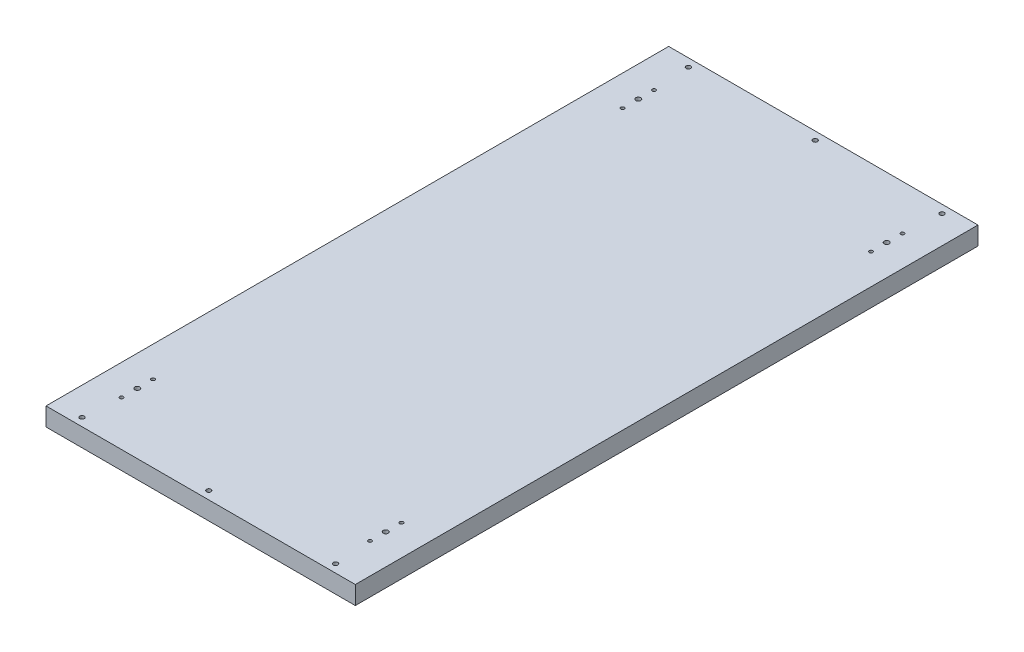
SolidWorks part; units mm, degrees
ref_plane "Front Plane" through (0, 0, 0) normal (0, 0, 1) x (1, 0, 0)
ref_plane "Top Plane" through (0, 0, 0) normal (0, 1, 0) x (1, 0, 0)
ref_plane "Right Plane" through (0, 0, 0) normal (1, 0, 0) x (0, 0, -1)
other "Bounding Box"
ref_plane "Default Plane" through (152.5, 9, -307) normal (-1, 0, 0) x (0, 0, 1)
sketch "Sketch1" plane through (0, 0, 0) normal (0, 1, 0) x (1, 0, 0)
  line L0 (-152.5, 307) -> (152.5, -307) construction
  line L1 (-152.5, 307) -> (152.5, 307)
  line L2 (-152.5, 307) -> (-152.5, -307)
  line L3 (-152.5, -307) -> (152.5, -307)
  line L4 (152.5, 307) -> (152.5, -307)
  line L5 (152.5, 307) -> (-152.5, -307) construction
  point P0 (0, 0)
  dimension "D1" = 305
  dimension "D2" = 614
extrude "Boss-Extrude1" add sketch "Sketch1" along normal mid plane 18 contours L4 L3 L2 L1
hole_wizard "CSK for #8 Flat Head Machine Screw (100)1" positions "Sketch2" profile "Sketch3" countersink size "#8" standard "ANSI Inch" end condition through all
sketch "Sketch2" plane through (-75, -9, 0) normal (0, -1, 0) x (0, 0, -1)
  line L3 (-307, -77.5) -> (-307, 227.5) construction
  line L4 (307, 227.5) -> (-307, 227.5) construction
  line L5 (-307, 75) -> (307, 75) construction
  line L6 (307, -77.5) -> (307, 227.5) construction
  point P9 (-299, 75)
  point P14 (-299, -50)
  point P23 (-299, 200)
  dimension "D1" = 8
  dimension "D2" = 125
sketch "Sketch3" plane through (0, -9, 299) normal (1, 0, 0) x (0, 0, -1)
  line L0 (0, 0) -> (0, 18)
  line L1 (0, 18) -> (2.2479, 18)
  line L2 (2.2479, 18) -> (2.2479, 1.6518)
  line L3 (2.2479, 1.6518) -> (4.2164, 0)
  line L5 (4.2164, 0) -> (0, 0)
  line L6 (-2.2479, 1.6518) -> (-4.2164, 0) construction
  line L11 (0, -6.35) -> (0, 107.95) construction
  dimension "Thru Hole Dia." = 4.4958
  dimension "Thru Hole Depth" = 18
  dimension "Near C'Sink Dia." = 8.4328
  dimension "Near C'Sink Angle" = 100
mirror "Mirror1" about plane through (0, 0, 0) normal (0, 0, 1) of "CSK for #8 Flat Head Machine Screw (100)1"
hole_wizard "#8-36 Tapped Hole1" positions "Sketch6" profile "Sketch5" tap size "#8-36" standard "ANSI Inch" end condition through all
sketch "Sketch6" plane through (0, -9, 0) normal (0, -1, 0) x (-1, 0, 0)
  line L0 (122.5, -262.5) -> (122.5, -231.5) construction
  line L2 (152.5, 307) -> (152.5, -307) construction
  line L3 (152.5, -307) -> (-152.5, -307) construction
  point P0 (122.5, -262.5)
  point P2 (122.5, -231.5)
  point P10 (122.5, -247)
  dimension "D1" = 30
  dimension "D2" = 60
  dimension "D3" = 31
sketch "Sketch5" plane through (-122.5, -9, 262.5) normal (1, 0, 0) x (0, 0, -1)
  line L0 (0, 0) -> (0, 18)
  line L1 (0, 18) -> (1.7272, 18)
  line L2 (1.7272, 18) -> (1.7272, 0)
  line L5 (1.7272, 0) -> (0, 0)
  line L11 (0, -6.35) -> (0, 107.95) construction
  dimension "Thru Tap Drill Dia." = 3.4544
  dimension "Thru Tap Drill Depth" = 18
cosmetic thread "Hole Thread1" parameters "D2"=4.1656
cosmetic thread "Hole Thread2" parameters "D2"=4.1656
hole_wizard "#8 Clearance Hole1" positions "Sketch9" profile "Sketch8" hole size "#8" standard "ANSI Inch" end condition through all
sketch "Sketch9" plane through (0, -9, 0) normal (0, -1, 0) x (-1, 0, 0)
  line L0 (122.5, -231.5) -> (122.5, -262.5) construction
  point P0 (122.5, -247)
sketch "Sketch8" plane through (-122.5, -9, 247) normal (1, 0, 0) x (0, 0, -1)
  line L0 (0, 0) -> (0, 18)
  line L1 (0, 18) -> (2.4574, 18)
  line L2 (2.4574, 18) -> (2.4574, 0)
  line L5 (2.4574, 0) -> (0, 0)
  line L11 (0, -6.35) -> (0, 107.95) construction
  dimension "Thru Hole Dia." = 4.9149
  dimension "Thru Hole Depth" = 18
mirror "Mirror2" about plane through (0, 0, 0) normal (0, 0, 1) of "#8-36 Tapped Hole1", "#8 Clearance Hole1" second plane through (0, 0, 0) second plane normal (1, 0, 0)
cosmetic thread "Hole Thread3" parameters "D2"=4.1656
cosmetic thread "Hole Thread4" parameters "D2"=4.1656
cosmetic thread "Hole Thread5" parameters "D2"=4.1656
cosmetic thread "Hole Thread6" parameters "D2"=4.1656
cosmetic thread "Hole Thread7" parameters "D2"=4.1656
cosmetic thread "Hole Thread8" parameters "D2"=4.1656
